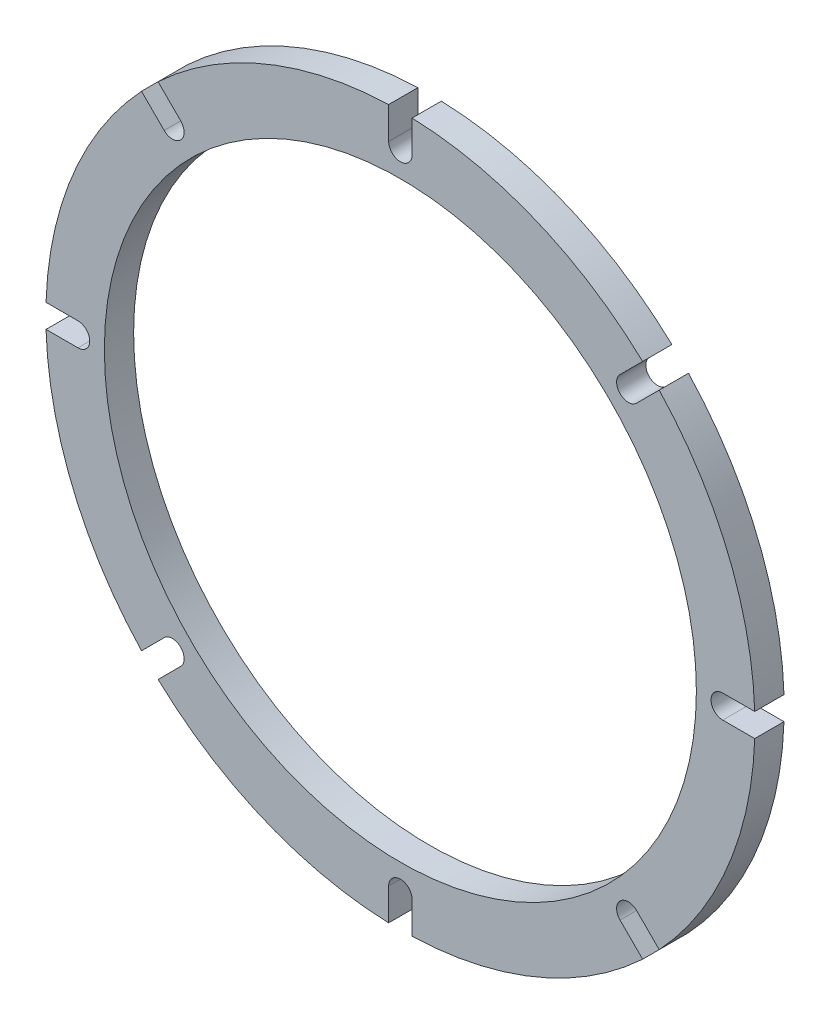
SolidWorks part; units mm, degrees
ref_plane "Front Plane" through (0, 0, 0) normal (0, 0, 1) x (1, 0, 0)
ref_plane "Top Plane" through (0, 0, 0) normal (0, 1, 0) x (1, 0, 0)
ref_plane "Right Plane" through (0, 0, 0) normal (1, 0, 0) x (0, 0, -1)
sketch "Sketch1" plane through (0, 0, 0) normal (0, 0, 1) x (1, 0, 0)
  circle A0 centre (0, 0) radius 121.15
  circle A1 centre (0, 0) radius 101.15
  dimension "D1" = 202.3
  dimension "D2" = 20
extrude "Boss-Extrude1" add sketch "Sketch1" along normal blind 10
sketch "Sketch2" plane through (0, 0, 0) normal (0, 0, 1) x (1, 0, 0)
  line L0 (0, -5.5) -> (0, 5.5) construction
  line L1 (5.5, 0) -> (-5.5, 0) construction
  line L2 (-4, 110.15) -> (-4, 123.852)
  line L3 (-4, 123.852) -> (4, 123.852)
  line L4 (4, 123.852) -> (4, 110.15)
  arc A0 (-4, 110.15) -> (4, 110.15) centre (0, 110.15) ccw
  dimension "D1" = 110.15
  dimension "D2" = 8
extrude "Cut-Extrude1" cut sketch "Sketch2" along normal blind 10
pattern_circular "CirPattern1" count 8 over 360 about axis through (0, 0, 0) along (0, 0, 1) of "Cut-Extrude1"
